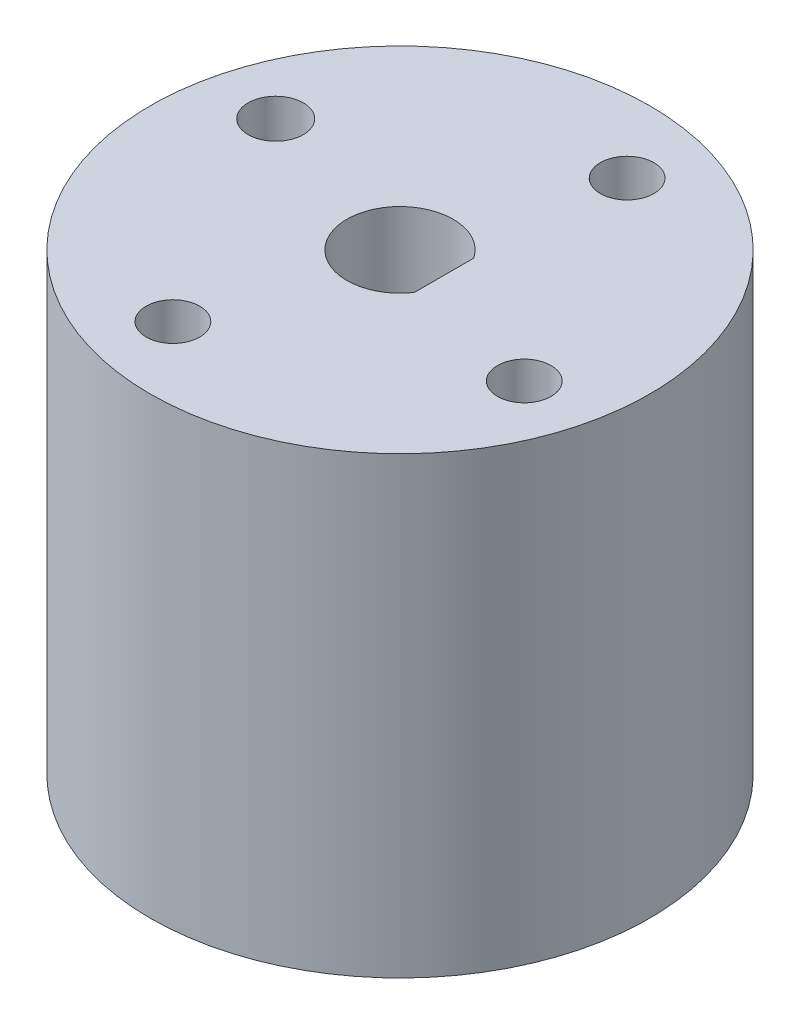
SolidWorks part; units mm, degrees
ref_plane "Front" through (0, 0, 0) normal (0, 0, 1) x (1, 0, 0)
ref_plane "Top" through (0, 0, 0) normal (0, 1, 0) x (1, 0, 0)
ref_plane "Right" through (0, 0, 0) normal (1, 0, 0) x (0, 0, -1)
sketch "Sketch1" plane through (0, 0, 0) normal (0, 1, 0) x (1, 0, 0)
  circle A0 centre (0, 0) radius 13.97
  circle A5 centre (2.8762, 9.8282) radius 1.5
  circle A6 centre (-9.8282, 2.8762) radius 1.5439
  circle A7 centre (-2.8762, -9.8282) radius 1.5
  circle A8 centre (9.8282, -2.8762) radius 1.5
  dimension "D1" = 27.94
extrude "Boss-Extrude1" add sketch "Sketch1" along normal blind 25.4
sketch "Sketch2" plane through (0, 25.4, 0) normal (0, 1, 0) x (1, 0, 0)
  line L0 (2.4653, 1.66) -> (2.4653, -1.66)
  circle A0 centre (0, 0) radius 2.9721
  dimension "D1" = 3.32
extrude "Cut-Extrude1" cut sketch "Sketch2" against normal blind 30 contours L0 A0
